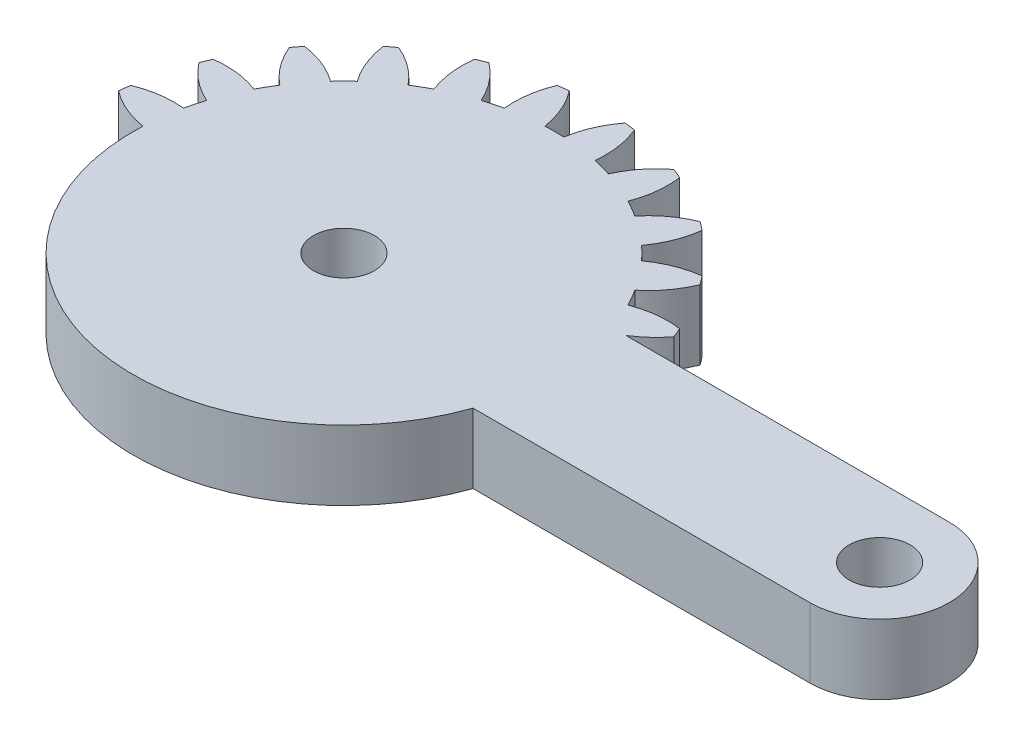
SolidWorks part; units mm, degrees
ref_plane "Front Plane" through (0, 0, 0) normal (0, 0, 1) x (1, 0, 0)
ref_plane "Top Plane" through (0, 0, 0) normal (0, 1, 0) x (1, 0, 0)
ref_plane "Right Plane" through (0, 0, 0) normal (1, 0, 0) x (0, 0, -1)
ref_plane "Plane1" through (0, 4, 0) normal (0, 1, 0) x (1, 0, 0)
sketch "Sketch1" plane through (0, 4, 0) normal (0, 1, 0) x (1, 0, 0)
  line L0 (1.3057, -4) -> (20.6437, -4)
  line L1 (20.6437, 4) -> (2.0816, 4)
  arc A0 (-24.5622, 2.2179) -> (-24.6437, 1.5991) centre (-10.1063, 0) ccw
  arc A1 (-24.6437, 1.5991) -> (-22.1869, 0.5427) centre (-21.3486, 5.8773) ccw
  arc A2 (-22.1869, 0.5427) -> (1.3057, -4) centre (-10.1063, 0) ccw
  arc A3 (20.6437, -4) -> (20.6437, 4) centre (20.6437, 0) ccw
  arc A4 (2.0816, 4) -> (3.5217, 5.3071) centre (-0.7683, 8.5867) ccw
  arc A5 (3.5217, 5.3071) -> (3.2829, 5.8838) centre (-10.1063, 0) ccw
  arc A6 (3.2829, 5.8838) -> (0.6271, 5.5703) centre (2.5684, 0.5313) ccw
  arc A7 (0.6271, 5.5703) -> (0.0844, 6.5103) centre (-10.1063, 0) ccw
  arc A8 (0.0844, 6.5103) -> (1.6838, 8.6535) centre (-3.3089, 10.711) ccw
  arc A9 (1.6838, 8.6535) -> (1.3038, 9.1487) centre (-10.1063, 0) ccw
  arc A10 (1.3038, 9.1487) -> (-1.1803, 8.1585) centre (1.999, 3.7936) ccw
  arc A11 (-1.1803, 8.1585) -> (-1.9479, 8.926) centre (-10.1063, 0) ccw
  arc A12 (-1.9479, 8.926) -> (-0.9576, 11.4102) centre (-6.3127, 12.1053) ccw
  arc A13 (-0.9576, 11.4102) -> (-1.4528, 11.7901) centre (-10.1063, 0) ccw
  arc A14 (-1.4528, 11.7901) -> (-3.596, 10.1907) centre (0.6046, 6.7975) ccw
  arc A15 (-3.596, 10.1907) -> (-4.5361, 10.7334) centre (-10.1063, 0) ccw
  arc A16 (-4.5361, 10.7334) -> (-4.2225, 13.3892) centre (-9.5751, 12.6747) ccw
  arc A17 (-4.2225, 13.3892) -> (-4.7992, 13.6281) centre (-10.1063, 0) ccw
  arc A18 (-4.7992, 13.6281) -> (-6.4554, 11.5285) centre (-1.5196, 9.3381) ccw
  arc A19 (-6.4554, 11.5285) -> (-7.5039, 11.8094) centre (-10.1063, 0) ccw
  arc A20 (-7.5039, 11.8094) -> (-7.8884, 14.4558) centre (-12.8736, 12.3803) ccw
  arc A21 (-7.8884, 14.4558) -> (-8.5072, 14.5373) centre (-10.1063, 0) ccw
  arc A22 (-8.5072, 14.5373) -> (-9.5636, 12.0806) centre (-4.2291, 11.2423) ccw
  arc A23 (-9.5636, 12.0806) -> (-10.6491, 12.0806) centre (-10.1063, 0) ccw
  arc A24 (-10.6491, 12.0806) -> (-11.7054, 14.5373) centre (-15.9836, 11.2423) ccw
  arc A25 (-11.7054, 14.5373) -> (-12.3243, 14.4558) centre (-10.1063, 0) ccw
  arc A26 (-12.3243, 14.4558) -> (-12.7088, 11.8094) centre (-7.3391, 12.3803) ccw
  arc A27 (-12.7088, 11.8094) -> (-13.7573, 11.5285) centre (-10.1063, 0) ccw
  arc A28 (-13.7573, 11.5285) -> (-15.4135, 13.6281) centre (-18.6931, 9.3381) ccw
  arc A29 (-15.4135, 13.6281) -> (-15.9901, 13.3892) centre (-10.1063, 0) ccw
  arc A30 (-15.9901, 13.3892) -> (-15.6766, 10.7334) centre (-10.6376, 12.6747) ccw
  arc A31 (-15.6766, 10.7334) -> (-16.6166, 10.1907) centre (-10.1063, 0) ccw
  arc A32 (-16.6166, 10.1907) -> (-18.7599, 11.7901) centre (-20.8173, 6.7975) ccw
  arc A33 (-18.7599, 11.7901) -> (-19.255, 11.4102) centre (-10.1063, 0) ccw
  arc A34 (-19.255, 11.4102) -> (-18.2648, 8.926) centre (-13.9, 12.1053) ccw
  arc A35 (-18.2648, 8.926) -> (-19.0324, 8.1585) centre (-10.1063, 0) ccw
  arc A36 (-19.0324, 8.1585) -> (-21.5165, 9.1487) centre (-22.2117, 3.7936) ccw
  arc A37 (-21.5165, 9.1487) -> (-21.8965, 8.6535) centre (-10.1063, 0) ccw
  arc A38 (-21.8965, 8.6535) -> (-20.2971, 6.5103) centre (-16.9038, 10.711) ccw
  arc A39 (-20.2971, 6.5103) -> (-20.8398, 5.5703) centre (-10.1063, 0) ccw
  arc A40 (-20.8398, 5.5703) -> (-23.4956, 5.8838) centre (-22.7811, 0.5313) ccw
  arc A41 (-23.4956, 5.8838) -> (-23.7344, 5.3071) centre (-10.1063, 0) ccw
  arc A42 (-23.7344, 5.3071) -> (-21.6348, 3.6509) centre (-19.4444, 8.5867) ccw
  arc A43 (-21.6348, 3.6509) -> (-21.9157, 2.6025) centre (-10.1063, 0) ccw
  arc A44 (-21.9157, 2.6025) -> (-24.5622, 2.2179) centre (-22.4867, -2.7673) ccw
  circle A45 centre (20.6437, 0) radius 1.75
  circle A46 centre (-10.1063, 0) radius 1.75
  dimension "D1" = 3.5
  dimension "D2" = 14.625
  dimension "D3" = 5.4
  dimension "D4" = 0.0844
  dimension "D5" = 4
  dimension "D6" = 0.6046
  dimension "D7" = 1.3057
  dimension "D8" = 2.0816
  dimension "D9" = 3.5217
  dimension "D10" = 1.1803
  dimension "D11" = 1.5196
  dimension "D12" = 3.3089
  dimension "D13" = 4.7992
  dimension "D14" = 9.5751
  dimension "D15" = 11.7054
  dimension "D16" = 20.6437
  dimension "D17" = 15.4135
  dimension "D18" = 18.6931
  dimension "D19" = 21.3486
  dimension "D20" = 21.9157
  dimension "D21" = 22.1869
  dimension "D22" = 22.4867
  dimension "D23" = 23.4956
extrude "Boss-Extrude1" add sketch "Sketch1" against normal blind 4
